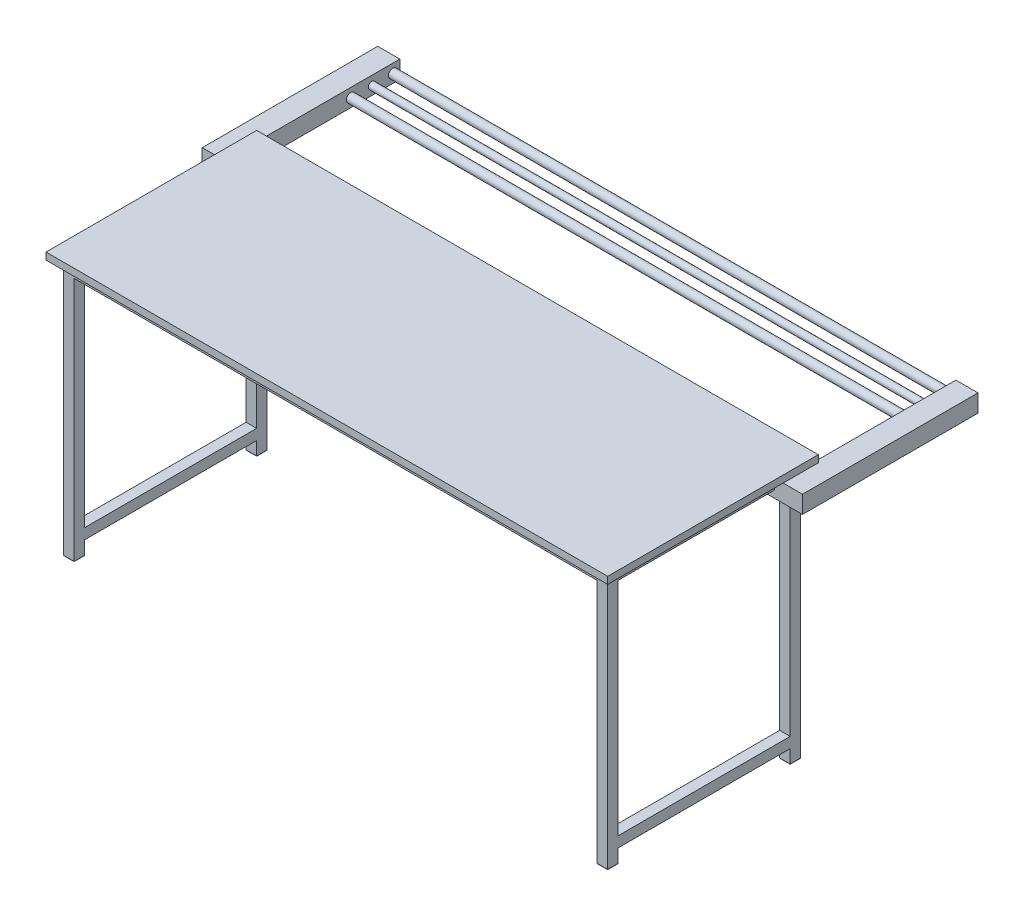
SolidWorks part; units mm, degrees
ref_plane "Front Plane" through (0, 0, 0) normal (0, 0, 1) x (1, 0, 0)
ref_plane "Top Plane" through (0, 0, 0) normal (0, 1, 0) x (1, 0, 0)
ref_plane "Right Plane" through (0, 0, 0) normal (1, 0, 0) x (0, 0, -1)
sketch "Sketch1" plane through (0, 0, 0) normal (0, 1, 0) x (1, 0, 0)
  line L1 (-800, 300) -> (800, 300)
  line L2 (-800, 300) -> (-800, -300)
  line L3 (-800, -300) -> (800, -300)
  line L4 (800, 300) -> (800, -300)
  line L5 (-800, 300) -> (800, -300) construction
  line L6 (-800, -300) -> (800, 300) construction
  point P0 (0, 0)
  dimension "D1" = 1600
  dimension "D2" = 600
extrude "Boss-Extrude1" add sketch "Sketch1" along normal blind 20
sketch "Sketch2" plane through (0, 0, 0) normal (0, -1, 0) x (1, 0, 0)
  line L4 (745, -245) -> (745, 245)
  line L5 (745, 245) -> (-745, 245)
  line L6 (-745, 245) -> (-745, -245)
  line L7 (-745, -245) -> (745, -245)
  line L8 (775, -275) -> (775, 275)
  line L9 (775, 275) -> (-775, 275)
  line L10 (-775, 275) -> (-775, -275)
  line L11 (-775, -275) -> (775, -275)
  line L12 (775, -275) -> (775, 275)
  line L13 (775, 275) -> (-775, 275)
  line L14 (-775, 275) -> (-775, -275)
  line L15 (-775, -275) -> (775, -275)
  dimension "D1" = 25
  dimension "D2" = 30
extrude "Boss-Extrude2" add sketch "Sketch2" along normal blind 30
sketch "Sketch3" plane through (0, -30, 0) normal (0, -1, 0) x (1, 0, 0)
  line L0 (-745, -245) -> (745, -245) construction
  line L1 (-775, -275) -> (-745, -275)
  line L2 (-775, -275) -> (-775, -245)
  line L3 (-775, -245) -> (-745, -245)
  line L4 (-745, -275) -> (-745, -245)
  line L5 (-745, -245) -> (745, -245) construction
  line L6 (745, -275) -> (745, -245)
  line L7 (745, -275) -> (775, -275)
  line L8 (775, -275) -> (775, -245)
  line L9 (745, -245) -> (775, -245)
  line L10 (775, -275) -> (775, 275) construction
  line L11 (-775, 245) -> (-775, 275)
  line L12 (-775, 245) -> (-745, 245)
  line L13 (-745, 245) -> (-745, 275)
  line L14 (-775, 275) -> (-745, 275)
  line L15 (745, 245) -> (745, 275)
  line L16 (745, 275) -> (775, 275)
  line L17 (775, 245) -> (775, 275)
  line L18 (745, 245) -> (775, 245)
  line L19 (775, 275) -> (-775, 275) construction
  dimension "D1" = 2
  dimension "D2" = 2
extrude "Boss-Extrude3" add sketch "Sketch3" along normal blind 700
sketch "Sketch4" plane through (0, -730, 0) normal (0, -1, 0) x (1, 0, 0)
  line L1 (-745, -275) -> (-775, -275)
  line L2 (-745, -275) -> (-745, 275)
  line L3 (-745, 275) -> (-775, 275)
  line L4 (-775, -275) -> (-775, 275)
  line L5 (775, -275) -> (745, -275)
  line L6 (775, -275) -> (775, 275)
  line L7 (775, 275) -> (745, 275)
  line L8 (745, -275) -> (745, 275)
extrude "Boss-Extrude4" add sketch "Sketch4" against normal blind 30 from offset 40 offset against normal yes
fillet "Fillet1" radius 2 16 edges at (745, -730, -260) (760, -730, -245) (775, -730, -260) (760, -730, -275) (745, -730, 260) (760, -730, 275) (775, -730, 260) (760, -730, 245) (-775, -730, 260) (-760, -730, 275) (-745, -730, 260) (-760, -730, 245) (-760, -730, -245) (-745, -730, -260) (-760, -730, -275) (-775, -730, -260)
sketch "Sketch5" plane through (0, 0, 0) normal (0, -1, 0) x (1, 0, 0)
  line L0 (-775, -275) -> (775, -275) construction
  line L2 (775, -275) -> (792, -275)
  line L3 (775, -275) -> (775, 275) construction
  line L4 (775, -200) -> (855, -200)
  line L5 (855, -200) -> (855, -700)
  line L6 (855, -700) -> (792, -700)
  line L7 (792, -700) -> (792, -275)
  line L8 (800, -300) -> (-800, -300) construction
  line L9 (800, 300) -> (800, -300) construction
  line L10 (775, -275) -> (775, -200)
  line L11 (0, 0) -> (0, -785.9299) construction
  line L12 (-775, -275) -> (-775, -200)
  line L13 (-775, -200) -> (-855, -200)
  line L14 (-855, -200) -> (-855, -700)
  line L15 (-855, -700) -> (-792, -700)
  line L16 (-792, -700) -> (-792, -275)
  line L17 (-775, -275) -> (-792, -275)
  dimension "D1" = 400
  dimension "D2" = 500
  dimension "D3" = 8
  dimension "D4" = 80
extrude "Boss-Extrude5" add sketch "Sketch5" along normal blind 50 separate body
sketch "Sketch6" plane through (0, 0, 0) normal (0, 1, 0) x (1, 0, 0)
  line L0 (-792, 560) -> (792, 560)
  line L1 (-792, 700) -> (-792, 275) construction
  line L2 (792, 275) -> (792, 700) construction
  line L3 (-792, 620) -> (792, 620) construction
  line L4 (-792, 680) -> (792, 680)
  line L5 (800, 300) -> (-800, 300) construction
  dimension "D1" = 120
  dimension "D2" = 60
  dimension "D3" = 320
sketch "Sketch7" plane through (792, 0, 0) normal (-1, 0, 0) x (0, 0, 1)
  line L0 (-700, -50) -> (-700, 0) construction
  circle A0 centre (-620, -25) radius 10
  point P2 (0, 0)
  point P4 (0, 0)
  point P7 (-700, -25)
  dimension "D1" = 20
extrude "Boss-Extrude6" add sketch "Sketch7" along normal up to surface (1584 mm away) up to face at (-792, -25, -487.5)
sketch "Sketch8" plane through (792, 0, 0) normal (-1, 0, 0) x (0, 0, 1)
  line L0 (-700, -50) -> (-700, 0) construction
  circle A0 centre (-680, -25) radius 12.5
  circle A1 centre (-560, -25) radius 12.5
  point P4 (0, 0)
  point P7 (-700, -25)
  dimension "D1" = 25
extrude "Boss-Extrude7" add sketch "Sketch8" along normal up to surface (1584 mm away) up to face at (-792, -25, -610)
sketch "Sketch15" plane through (0, -50, 0) normal (0, -1, 0) x (1, 0, 0)
  line L0 (775, -200) -> (775, -275) construction
  line L1 (775, -245) -> (695, -245)
  line L2 (775, -245) -> (775, -200)
  line L3 (775, -200) -> (695, -200)
  line L4 (695, -245) -> (695, -200)
  line L5 (775, -245) -> (745, -245) construction
  line L6 (855, -200) -> (775, -200) construction
  line L7 (745, -245) -> (745, 245) construction
  line L8 (0, 0) -> (0, -183.2025) construction
  line L9 (-775, -200) -> (-695, -200)
  line L10 (-695, -245) -> (-695, -200)
  line L11 (-775, -245) -> (-695, -245)
  line L12 (-775, -245) -> (-775, -200)
  dimension "D1" = 50
extrude "Boss-Extrude8" add sketch "Sketch15" against normal up to surface (20 mm away) up to face at (760, -30, 0)
sketch "Sketch16" plane through (0, 0, 0) normal (0, -1, 0) x (1, 0, 0)
  line L0 (745, -245) -> (745, 245) construction
  line L1 (745, -245) -> (745, -200)
  line L2 (0, 0) -> (0, -139.887) construction
  line L3 (-745, -200) -> (-695, -200)
  line L4 (695, -245) -> (775, -245)
  line L5 (695, -200) -> (695, -245)
  line L6 (775, -200) -> (695, -200)
  line L7 (775, -245) -> (775, -200)
  line L8 (695, -245) -> (745, -245)
  line L9 (695, -200) -> (695, -245)
  line L10 (745, -200) -> (695, -200)
  line L12 (-745, -245) -> (-745, -200)
  line L13 (-695, -245) -> (-745, -245)
  line L14 (-695, -200) -> (-695, -245)
  dimension "D1" = 0
extrude "Boss-Extrude9" add sketch "Sketch16" along normal up to surface (50 mm away) up to face at (779.25, -50, -355)
